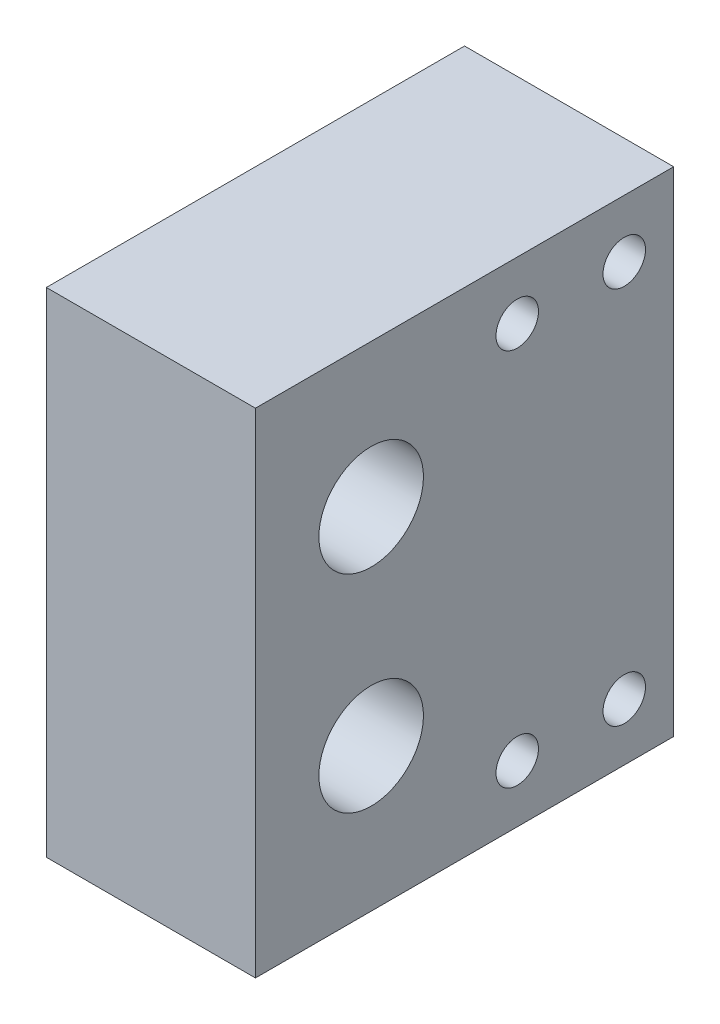
SolidWorks part; units mm, degrees
material "6061 Alloy"
ref_plane "Front Plane" through (0, 0, 0) normal (0, 0, 1) x (1, 0, 0)
ref_plane "Top Plane" through (0, 0, 0) normal (0, 1, 0) x (1, 0, 0)
ref_plane "Right Plane" through (0, 0, 0) normal (1, 0, 0) x (0, 0, -1)
sketch "Sketch1" plane through (0, 0, 0) normal (0, 0, 1) x (1, 0, 0)
  line L1 (-12.7, 29.972) -> (12.7, 29.972)
  line L2 (-12.7, 29.972) -> (-12.7, -29.972)
  line L3 (-12.7, -29.972) -> (12.7, -29.972)
  line L4 (12.7, 29.972) -> (12.7, -29.972)
  line L5 (-12.7, 29.972) -> (12.7, -29.972) construction
  line L6 (-12.7, -29.972) -> (12.7, 29.972) construction
  point P0 (0, 0)
  dimension "D1" = 59.944
  dimension "D2" = 25.4
extrude "Boss-Extrude1" add sketch "Sketch1" along normal blind 50.8
sketch "Sketch2" plane through (12.7, 0, 0) normal (1, 0, 0) x (0, 0, -1)
  line L4 (0, -29.972) -> (0, 29.972)
  line L5 (0, 29.972) -> (-50.8, 29.972)
  line L6 (-50.8, 29.972) -> (-50.8, -29.972)
  line L7 (-50.8, -29.972) -> (0, -29.972)
  line L8 (0, -29.972) -> (0, 29.972)
  line L9 (0, 29.972) -> (-50.8, 29.972)
  line L10 (-50.8, 29.972) -> (-50.8, -29.972)
  line L11 (-50.8, -29.972) -> (0, -29.972)
  circle A1 centre (-19, 22.972) radius 2.5797
  circle A3 centre (-6, 22.972) radius 2.5797
  circle A5 centre (-19, -23.028) radius 2.5797
  circle A7 centre (-6, -23.028) radius 2.5797
  dimension "D2" = 5.1594
  dimension "D3" = 5.1594
  dimension "D4" = 5.1594
  dimension "D5" = 5.1594
  dimension "D1" = 0
extrude "Cut-Extrude1" cut sketch "Sketch2" against normal blind 10.16 flip side to cut
sketch "Sketch3" plane through (12.7, 0, 0) normal (1, 0, 0) x (0, 0, -1)
  line L0 (-50.8, 29.972) -> (0, 29.972) construction
  line L1 (-50.8, -29.972) -> (0, -29.972) construction
  circle A0 centre (-36.7438, 12.573) radius 3.302
  circle A1 centre (-36.7438, -12.573) radius 3.302
  dimension "D1" = 17.399
  dimension "D2" = 17.399
extrude "Cut-Extrude2" cut sketch "Sketch3" against normal up to next
sketch "Sketch4" plane through (12.7, 0, 0) normal (1, 0, 0) x (0, 0, -1)
  circle A0 centre (-36.7438, 12.573) radius 6.35
  circle A1 centre (-36.7438, -12.573) radius 6.35
extrude "Cut-Extrude3" cut sketch "Sketch4" against normal blind 19.05
